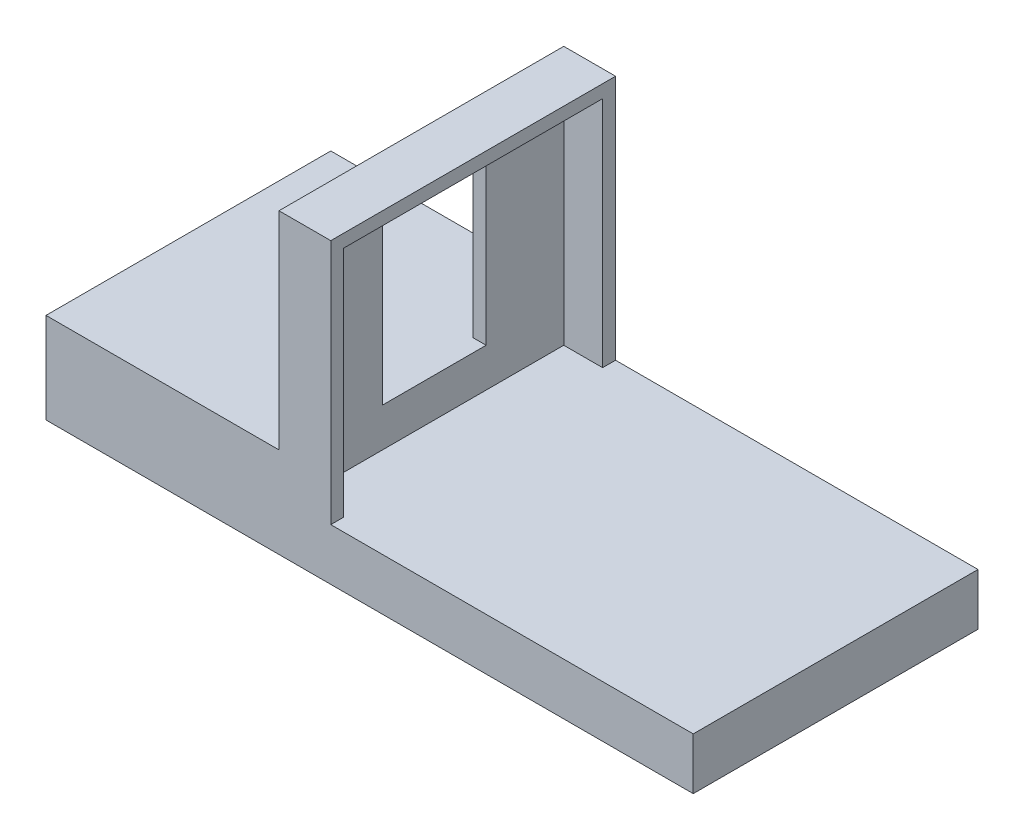
SolidWorks part; units mm, degrees
ref_plane "Front Plane" through (0, 0, 0) normal (0, 0, 1) x (1, 0, 0)
ref_plane "Top Plane" through (0, 0, 0) normal (0, 1, 0) x (1, 0, 0)
ref_plane "Right Plane" through (0, 0, 0) normal (1, 0, 0) x (0, 0, -1)
sketch "Sketch1" plane through (0, 0, 0) normal (0, 1, 0) x (1, 0, 0)
  line L1 (-125, 55) -> (125, 55)
  line L2 (-125, 55) -> (-125, -55)
  line L3 (-125, -55) -> (125, -55)
  line L4 (125, 55) -> (125, -55)
  point P4 (125, 0)
  dimension "D1" = 250
  dimension "D2" = 125
  dimension "D3" = 110
  dimension "D4" = 55
extrude "Boss-Extrude1" add sketch "Sketch1" along normal blind 20
sketch "Sketch2" plane through (0, 20, 0) normal (0, 1, 0) x (1, 0, 0)
  line L0 (-125, -55) -> (125, -55) construction
  line L1 (-125, 55) -> (-15, 55)
  line L2 (-125, 55) -> (-125, -55)
  line L3 (-125, -55) -> (-15, -55)
  line L4 (-15, 55) -> (-15, -55)
  dimension "D1" = 110
extrude "Boss-Extrude2" add sketch "Sketch2" along normal blind 15
sketch "Sketch3" plane through (0, 35, 0) normal (0, 1, 0) x (1, 0, 0)
  line L0 (-125, -55) -> (-15, -55) construction
  line L1 (-15, 55) -> (-35, 55)
  line L2 (-15, 55) -> (-15, -55)
  line L3 (-15, -55) -> (-35, -55)
  line L4 (-35, 55) -> (-35, -55)
  dimension "D1" = 20
extrude "Boss-Extrude3" add sketch "Sketch3" along normal blind 80
sketch "Sketch4" plane through (-35, 0, 0) normal (-1, 0, 0) x (0, 0, 1)
  line L0 (-55, 35) -> (55, 35) construction
  line L1 (-20, 100.5961) -> (20, 100.5961)
  line L2 (-20, 100.5961) -> (-20, 35)
  line L3 (-20, 35) -> (20, 35)
  line L4 (20, 100.5961) -> (20, 35)
  dimension "D1" = 40
  dimension "D2" = 20
extrude "Cut-Extrude1" cut sketch "Sketch4" against normal blind 80
sketch "Sketch6" plane through (0, 0, 0) normal (0, -1, 0) x (1, 0, 0)
  line L1 (-120, 50) -> (120, 50)
  line L2 (-120, 50) -> (-120, -50)
  line L3 (-120, -50) -> (120, -50)
  line L4 (120, 50) -> (120, -50)
  dimension "D1" = 100
  dimension "D2" = 240
  dimension "D3" = 120
  dimension "D4" = 50
extrude "Cut-Extrude2" cut sketch "Sketch6" against normal blind 15
sketch "Sketch7" plane through (0, 15, 0) normal (0, -1, 0) x (-1, 0, 0)
  line L0 (120, 50) -> (-120, 50) construction
  line L1 (120, -50) -> (35, -50)
  line L2 (120, -50) -> (120, 50)
  line L3 (120, 50) -> (35, 50)
  line L4 (35, -50) -> (35, 50)
  dimension "D1" = 85
extrude "Cut-Extrude3" cut sketch "Sketch7" against normal blind 15 contours L2 L1 L4 L3
sketch "Sketch9" plane through (0, 15, 0) normal (0, -1, 0) x (1, 0, 0)
  line L0 (120, 50) -> (-120, 50) construction
  line L1 (-30, 50) -> (-12.7753, 50)
  line L2 (-30, 50) -> (-30, -50)
  line L3 (-30, -50) -> (-12.7753, -50)
  line L4 (-12.7753, 50) -> (-12.7753, -50)
  line L5 (-35, -50) -> (120, -50) construction
  line L6 (-35, 50) -> (-35, -50) construction
  dimension "D1" = 5
extrude "Cut-Extrude4" cut sketch "Sketch9" against normal blind 95
sketch "Sketch10" plane through (0, 15, 0) normal (0, -1, 0) x (-1, 0, 0)
  line L1 (30, -50) -> (12.7753, -50)
  line L2 (30, -50) -> (30, 50)
  line L3 (30, 50) -> (12.7753, 50)
  line L4 (12.7753, -50) -> (12.7753, 50)
extrude "Boss-Extrude4" add sketch "Sketch10" against normal blind 5
